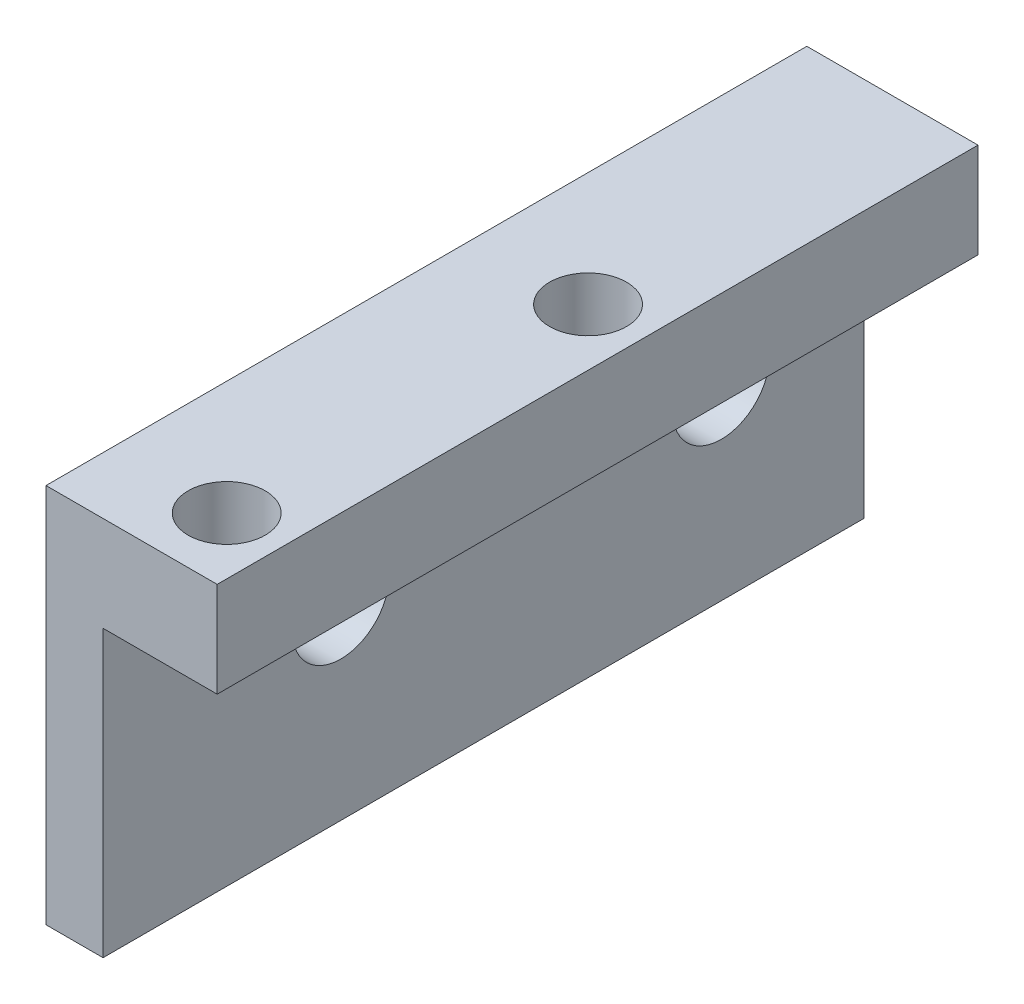
SolidWorks part; units mm, degrees
ref_plane "Front Plane" through (0, 0, 0) normal (0, 0, 1) x (1, 0, 0)
ref_plane "Top Plane" through (0, 0, 0) normal (0, 1, 0) x (1, 0, 0)
ref_plane "Right Plane" through (0, 0, 0) normal (1, 0, 0) x (0, 0, -1)
sketch "Sketch1" plane through (0, 0, 0) normal (0, 1, 0) x (1, 0, 0)
  line L1 (0, 0) -> (9, 0)
  line L2 (0, 0) -> (0, 40)
  line L3 (0, 40) -> (9, 40)
  line L4 (9, 0) -> (9, 40)
  circle A0 centre (6, 3.4994) radius 2.025
  circle A1 centre (6, 22.4994) radius 2.025
  point P9 (0, 0)
  point P10 (6, 3.4994)
  dimension "D2" = 19
  dimension "D4" = 4.05
  dimension "D5" = 4.05
  dimension "D1" = 9
  dimension "D3" = 40
  dimension "D6" = 3
  dimension "D7" = 3
extrude "Boss-Extrude1" add sketch "Sketch1" against normal blind 5
sketch "Sketch2" plane through (0, -5, 0) normal (0, -1, 0) x (1, 0, 0)
  line L1 (0, 0) -> (3, 0)
  line L2 (0, 0) -> (0, -40)
  line L3 (0, -40) -> (3, -40)
  line L4 (3, 0) -> (3, -40)
  line L5 (0, 0) -> (9, 0) construction
  line L6 (9, -40) -> (0, -40) construction
  point P5 (2.8998, -40)
  point P7 (0, 0)
  point P8 (2.8998, 0)
  point P11 (4.5, -40)
  dimension "D1" = 3
extrude "Boss-Extrude2" add sketch "Sketch2" along normal blind 15
sketch "Sketch3" plane through (3, 0, 0) normal (1, 0, 0) x (0, 0, -1)
  line L0 (0, -10.1) -> (40, -10.1) construction
  line L1 (0, -20) -> (0, -5) construction
  line L2 (40, -20) -> (40, -5) construction
  line L3 (40, -20) -> (0, -20) construction
  circle A0 centre (12.5, -10.1) radius 2.55
  circle A1 centre (32.5, -10.1) radius 2.55
  point P12 (13.4052, -10)
  point P13 (33.6093, -10)
  dimension "D3" = 5.1
  dimension "D4" = 5.1
  dimension "D1" = 9.9
  dimension "D2" = 20
  dimension "D5" = 7.5
extrude "Cut-Extrude1" cut sketch "Sketch3" against normal through all
